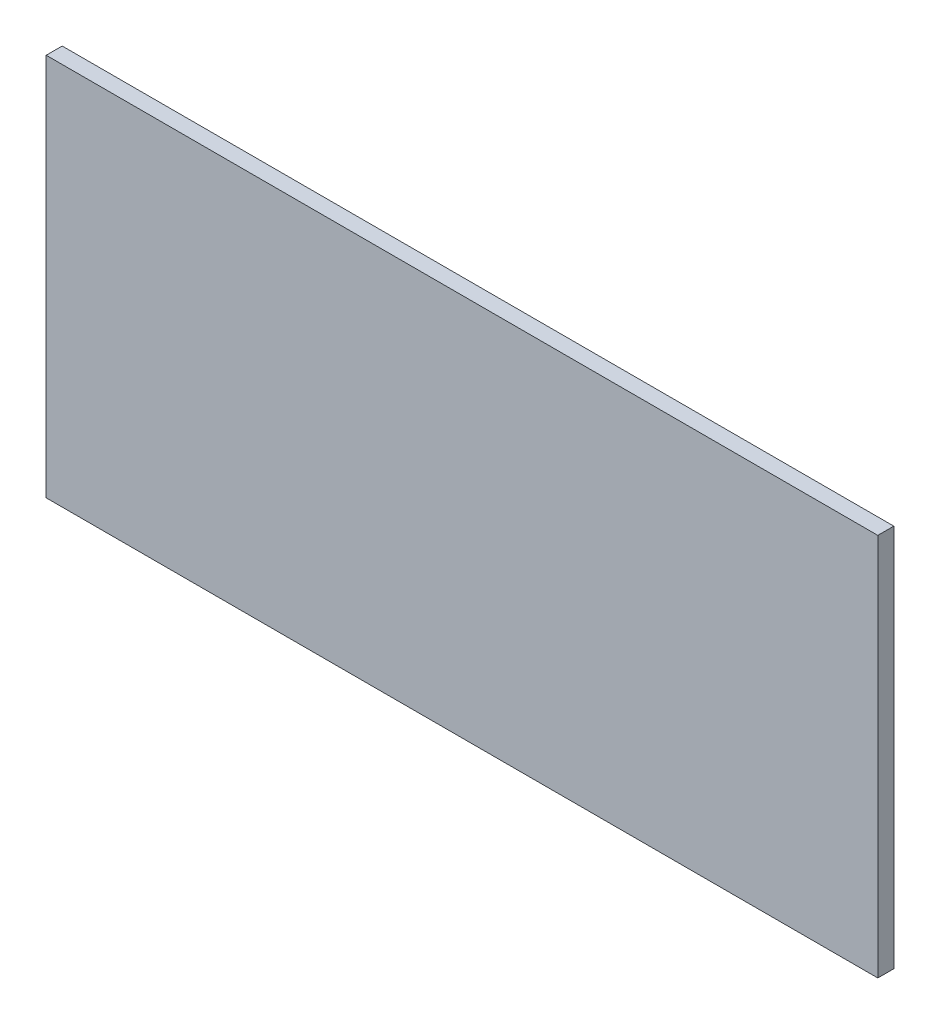
SolidWorks part; units mm, degrees
material "5052-H36"
ref_plane "X-Y Datum" through (0, 0, 0) normal (0, 0, 1) x (1, 0, 0)
ref_plane "X-Z Datum" through (0, 0, 0) normal (0, 1, 0) x (1, 0, 0)
ref_plane "Y-Z Datum" through (0, 0, 0) normal (1, 0, 0) x (0, 0, -1)
sketch "Sketch1" plane through (0, 0, 0) normal (0, 0, 1) x (1, 0, 0)
  line L1 (-154.6125, 44.322) -> (154.6125, 44.322)
  line L2 (-154.6125, 44.322) -> (-154.6125, -44.322)
  line L3 (-154.6125, -44.322) -> (154.6125, -44.322)
  line L4 (154.6125, 44.322) -> (154.6125, -44.322)
  line L5 (-154.6125, 44.322) -> (154.6125, -44.322) construction
  line L6 (-154.6125, -44.322) -> (154.6125, 44.322) construction
  point P0 (0, 0)
  dimension "D1" = 88.644
  dimension "D2" = 309.225
extrude "Boss-Extrude1" add sketch "Sketch1" along normal blind 2.286
sketch "Sketch2" plane through (0, 0, 2.286) normal (0, 0, 1) x (1, 0, 0)
  line L0 (154.6125, 10.4737) -> (-154.6125, 10.4737)
  line L1 (154.6125, -44.322) -> (154.6125, 44.322) construction
  line L2 (-154.6125, 44.322) -> (-154.6125, -44.322) construction
  line L3 (-99.2094, 44.322) -> (-99.2094, 10.4737)
  line L4 (154.6125, 44.322) -> (-154.6125, 44.322) construction
  line L5 (39.7289, 44.322) -> (39.7289, 10.4737)
  line L6 (-11.9508, 44.322) -> (-11.9508, -44.322)
  line L11 (154.6125, -44.322) -> (154.6125, 44.322)
  line L12 (154.6125, 44.322) -> (-154.6125, 44.322)
  line L13 (-154.6125, 44.322) -> (-154.6125, -44.322)
  line L14 (-154.6125, -44.322) -> (154.6125, -44.322)
  line L15 (154.6125, -44.322) -> (154.6125, 44.322)
  line L16 (154.6125, 44.322) -> (-154.6125, 44.322)
  line L17 (-154.6125, 44.322) -> (-154.6125, -44.322)
  line L18 (-154.6125, -44.322) -> (154.6125, -44.322)
  line M1 (154.6125, -44.322) -> (154.6125, 44.322)
  line M2 (154.6125, 44.322) -> (-154.6125, 44.322)
  line M3 (-154.6125, 44.322) -> (-154.6125, -44.322)
  dimension "D1" = 0
extrude "Cut-Extrude1" [suppressed] cut sketch "Sketch2" against normal through all contours L3 L0 M2 M3 | L5 L0 M2 M1
sketch "Sketch4" plane through (0, 0, 2.286) normal (0, 0, 1) x (1, 0, 0)
  line L0 (-11.9508, 44.322) -> (-11.9508, -44.322) construction
  line L1 (39.7289, 44.322) -> (39.7289, 10.4737) construction
  line L2 (-99.2094, 44.322) -> (-99.2094, 10.4737) construction
  line L3 (154.6125, 10.4737) -> (-154.6125, 10.4737) construction
  line L4 (154.6125, 44.322) -> (-154.6125, 44.322)
  line L5 (-154.6125, 44.322) -> (-154.6125, -44.322)
  line L6 (-154.6125, -44.322) -> (154.6125, -44.322)
  line L7 (154.6125, -44.322) -> (154.6125, 44.322)
  line L8 (154.6125, 44.322) -> (-154.6125, 44.322)
  line L9 (-154.6125, 44.322) -> (-154.6125, -44.322)
  line L10 (-154.6125, -44.322) -> (154.6125, -44.322)
  line L11 (154.6125, -44.322) -> (154.6125, 44.322)
  line L12 (-11.9508, 44.322) -> (-11.9508, -44.322)
  line L13 (39.7289, 44.322) -> (39.7289, 10.4737)
  line L14 (-99.2094, 44.322) -> (-99.2094, 10.4737)
  line L15 (154.6125, 10.4737) -> (-154.6125, 10.4737)
  line L16 (35.7399, 44.322) -> (35.7399, -44.322)
  line M6 (154.6125, 44.322) -> (-154.6125, 44.322)
  line M7 (-154.6125, 44.322) -> (-154.6125, -44.322)
  line M8 (-154.6125, -44.322) -> (154.6125, -44.322)
  dimension "D1" = 0
extrude "Cut-Extrude4" cut sketch "Sketch4" against normal through all contours L15 L11 L13 M6 | L15 L14 M6 M7 | L15 L12 L8 L14 | L12 L15 L9 M8 | L15 L13 L8 L12 | L16 L8 L13 L15 | L16 L15 L12 L10
